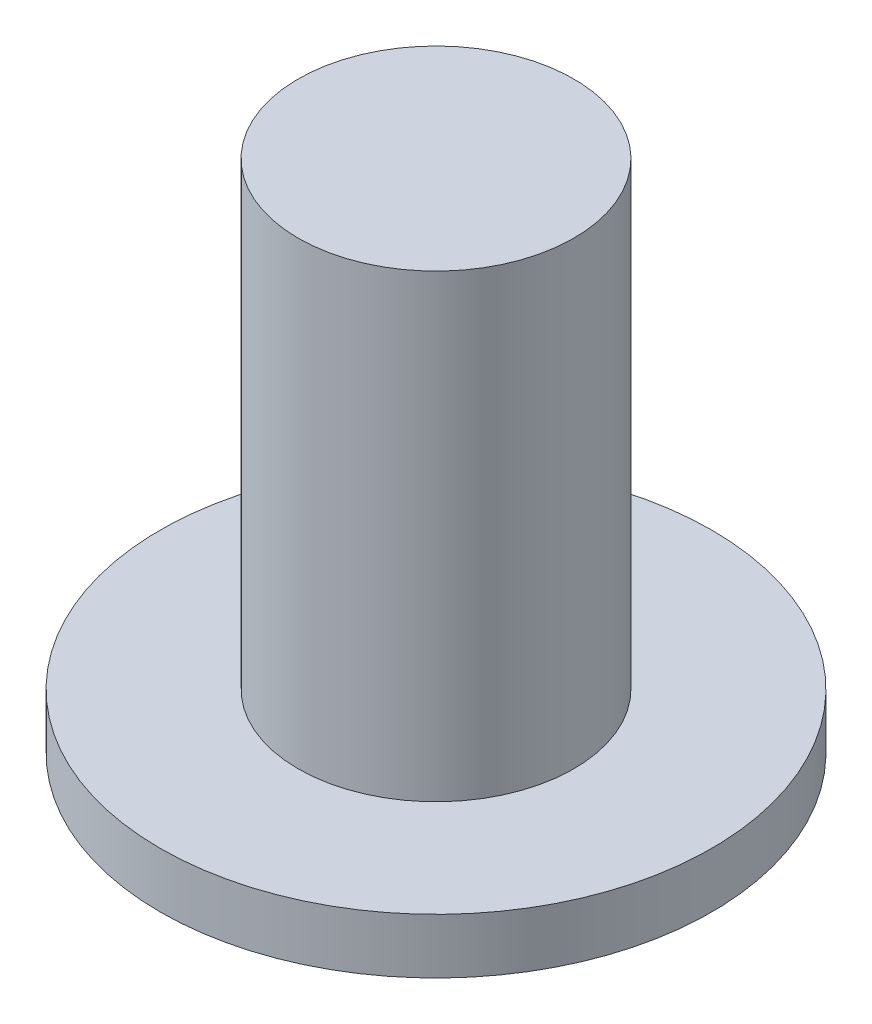
SolidWorks part; units mm, degrees
ref_plane "Front Plane" through (0, 0, 0) normal (0, 0, 1) x (1, 0, 0)
ref_plane "Top Plane" through (0, 0, 0) normal (0, 1, 0) x (1, 0, 0)
ref_plane "Right Plane" through (0, 0, 0) normal (1, 0, 0) x (0, 0, -1)
sketch "Sketch2" plane through (0, 0, 0) normal (0, 1, 0) x (1, 0, 0)
  circle A0 centre (0, 0) radius 150
  dimension "D1" = 300
extrude "Boss-Extrude1" add sketch "Sketch2" along normal blind 30
sketch "Sketch3" plane through (0, 30, 0) normal (0, 1, 0) x (1, 0, 0)
  circle A0 centre (0, 0) radius 75
  dimension "D1" = 150
extrude "Boss-Extrude2" add sketch "Sketch3" along normal blind 250
